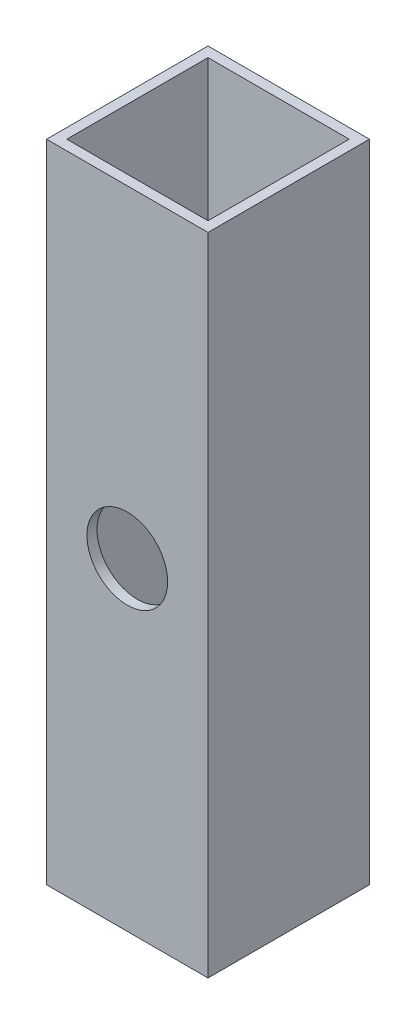
SolidWorks part; units mm, degrees
ref_plane "Front Plane" through (0, 0, 0) normal (0, 0, 1) x (1, 0, 0)
ref_plane "Top Plane" through (0, 0, 0) normal (0, 1, 0) x (1, 0, 0)
ref_plane "Right Plane" through (0, 0, 0) normal (1, 0, 0) x (0, 0, -1)
sketch "Sketch1" plane through (0, 0, 0) normal (0, 1, 0) x (1, 0, 0)
  line L1 (12.7, 12.7) -> (-12.7, 12.7)
  line L2 (12.7, 12.7) -> (12.7, -12.7)
  line L3 (12.7, -12.7) -> (-12.7, -12.7)
  line L4 (-12.7, 12.7) -> (-12.7, -12.7)
  line L5 (12.7, 12.7) -> (-12.7, -12.7) construction
  line L6 (12.7, -12.7) -> (-12.7, 12.7) construction
  line L7 (11.1125, 11.1125) -> (-11.1125, 11.1125)
  line L8 (11.1125, 11.1125) -> (11.1125, -11.1125)
  line L9 (11.1125, -11.1125) -> (-11.1125, -11.1125)
  line L10 (-11.1125, 11.1125) -> (-11.1125, -11.1125)
  line L11 (11.1125, 11.1125) -> (-11.1125, -11.1125) construction
  line L12 (11.1125, -11.1125) -> (-11.1125, 11.1125) construction
  point P0 (0, 0)
  point P6 (0, 0)
  dimension "D1" = 25.4
  dimension "D2" = 25.4
  dimension "D3" = 1.5875
  dimension "D4" = 1.5875
extrude "Boss-Extrude1" add sketch "Sketch1" along normal blind 101.6
sketch "Sketch2" plane through (0, 0, 12.7) normal (0, 0, 1) x (1, 0, 0)
  line L0 (-12.7, 0) -> (12.7, 0) construction
  line L1 (-12.7, 101.6) -> (-12.7, 0) construction
  circle A0 centre (0, 50.8) radius 6.35
  dimension "D1" = 12.7
  dimension "D2" = 50.8
  dimension "D3" = 12.7
extrude "Cut-Extrude1" cut sketch "Sketch2" against normal blind 101.6
